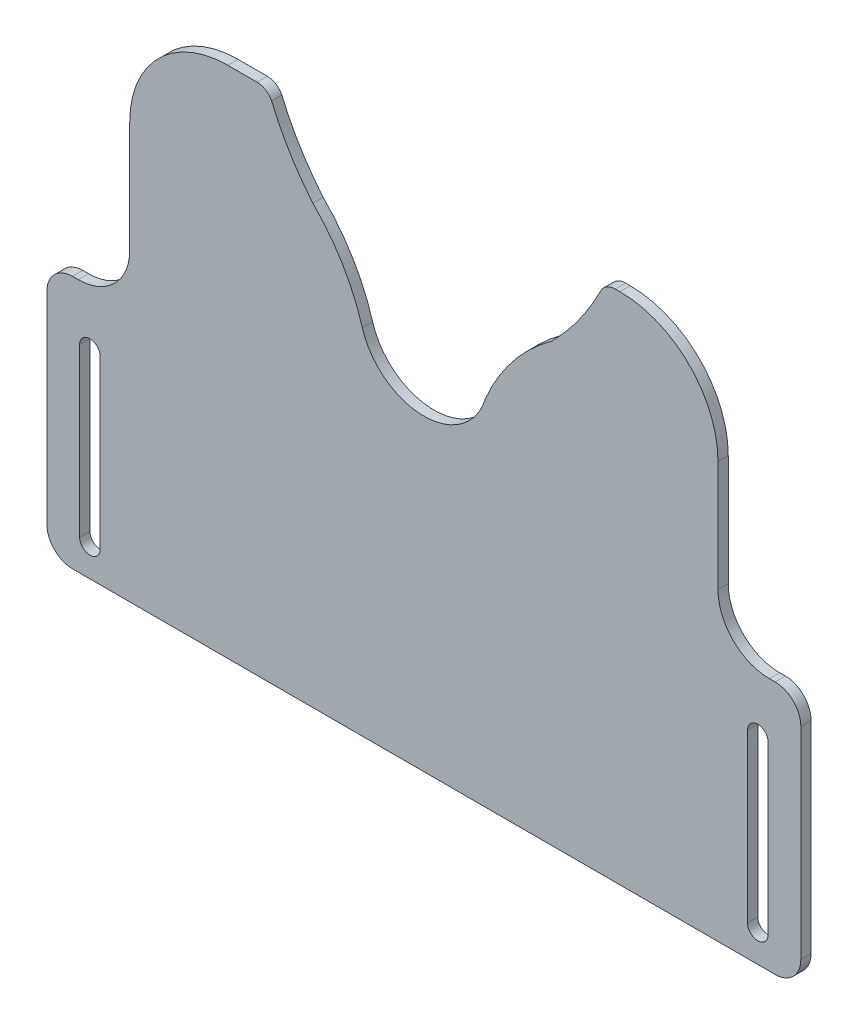
SolidWorks part; units mm, degrees
ref_plane "Front Plane" through (0, 0, 0) normal (0, 0, 1) x (1, 0, 0)
ref_plane "Top Plane" through (0, 0, 0) normal (0, 1, 0) x (1, 0, 0)
ref_plane "Right Plane" through (0, 0, 0) normal (1, 0, 0) x (0, 0, -1)
sketch "Sketch2" plane through (0, 0, 0) normal (0, 0, 1) x (1, 0, 0)
  line B0 (76.3333, 193.3656) -> (74.5053, 193.3656)
  line B1 (-64.9636, 193.3656) -> (-76.3333, 193.3656)
  line B2 (-114.5, 155.1989) -> (-114.5, -6.6344)
  line B3 (114.5, -6.6344) -> (114.5, 155.1989)
  arc B4 (114.5, 155.1989) -> (76.3333, 193.3656) centre (76.3333, 155.1989) ccw
  arc B5 (74.5053, 193.3656) -> (68.8157, 189.8492) centre (74.5053, 187.0044) ccw
  arc B6 (49.7507, 163.3979) -> (68.8157, 189.8492) centre (-22.2171, 235.3657) ccw
  arc B7 (49.7507, 163.3979) -> (23.9676, 131.1316) centre (94.2687, 101.3905) ccw
  arc B8 (-23.9676, 131.1316) -> (23.9676, 131.1316) centre (0, 138.2417) ccw
  arc B9 (-23.9676, 131.1316) -> (-43.1729, 163.3979) centre (-97.1487, 109.4221) ccw
  arc B10 (-59.274, 189.8492) -> (-43.1729, 163.3979) centre (34.7026, 228.9275) ccw
  arc B11 (-59.274, 189.8492) -> (-64.9636, 193.3656) centre (-64.9636, 187.0044) ccw
  arc B12 (-76.3333, 193.3656) -> (-114.5, 155.1989) centre (-76.3333, 155.1989) ccw
  line B13 (-114.5, -6.6344) -> (114.5, -6.6344)
sketch_block_instance "Block1-1"
sketch_block "Block1" parameters "D1"=11.3697, "D2"=229
extrude "Boss-Extrude1" add sketch "Sketch2" along normal blind 4
sketch "Sketch3" plane through (0, 0, 4) normal (0, 0, 1) x (1, 0, 0)
  line L0 (-114.5, -6.6344) -> (-146.7474, -6.6344)
  line L1 (-146.7474, -6.6344) -> (-146.7474, 92)
  line L2 (-146.7474, 92) -> (-114.5, 92)
  line L3 (-114.5, 155.1989) -> (-114.5, -6.6344) construction
  line L4 (-114.5, 92) -> (-114.5, -6.6344)
  line L5 (-130, 70.3656) -> (-130, 5.3656) construction
  line L6 (-126, 70.3656) -> (-126, 5.3656)
  line L7 (-134, 70.3656) -> (-134, 5.3656)
  line L8 (0, -6.6344) -> (0, 127.9164) construction
  line L9 (130, 70.3656) -> (130, 5.3656) construction
  line L10 (126, 70.3656) -> (126, 5.3656)
  line L11 (134, 70.3656) -> (134, 5.3656)
  line L12 (114.5, 92) -> (114.5, -6.6344)
  line L13 (146.7474, 92) -> (114.5, 92)
  line L14 (146.7474, -6.6344) -> (146.7474, 92)
  line L15 (114.5, -6.6344) -> (146.7474, -6.6344)
  line L16 (-114.5, -6.6344) -> (114.5, -6.6344) construction
  arc A0 (-126, 70.3656) -> (-134, 70.3656) centre (-130, 70.3656) ccw
  arc A1 (-134, 5.3656) -> (-126, 5.3656) centre (-130, 5.3656) ccw
  arc A2 (-131.771, 17.4523) -> (-128.229, 17.4523) centre (-130, 20.3547) ccw construction
  arc A3 (-103.5, 5.3656) -> (-95.5, 5.3656) centre (-99.5, 5.3656) ccw construction
  arc A4 (-103.5, 5.3656) -> (-95.5, 5.3656) centre (-99.5, 5.3656) ccw construction
  arc A5 (126, 70.3656) -> (134, 70.3656) centre (130, 70.3656) cw
  arc A6 (134, 5.3656) -> (126, 5.3656) centre (130, 5.3656) cw
  arc A7 (103.5, 5.3656) -> (95.5, 5.3656) centre (99.5, 5.3656) cw construction
  point P10 (-130, 37.8656)
  point P18 (-130, 16.9547)
  point P26 (130, 37.8656)
  dimension "D1" = 4
  dimension "D2" = 65
extrude "Boss-Extrude2" add sketch "Sketch3" against normal blind 4
fillet "Fillet1" radius 10 4 edges at (146.7474, 92, 2) (146.7474, -6.6344, 2) (-146.7474, -6.6344, 2) (-146.7474, 92, 2)
fillet "Fillet2" radius 20 2 edges at (-114.5, 92, 2)
